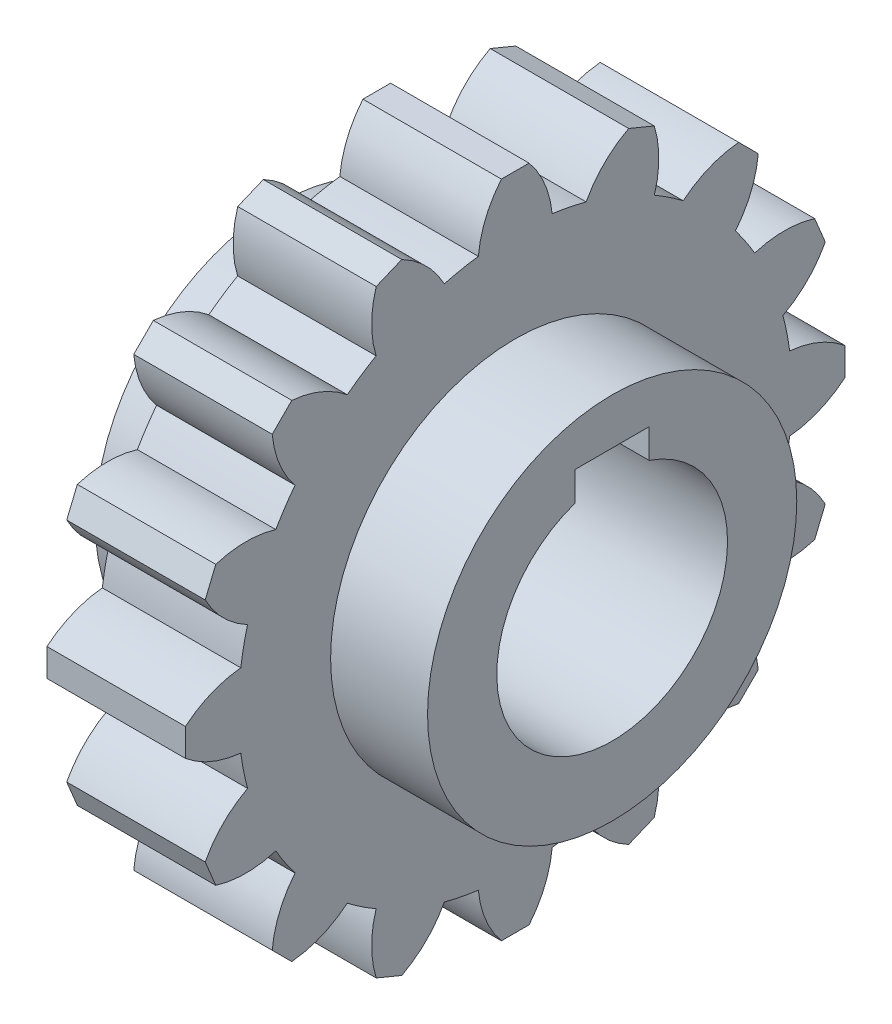
SolidWorks part; units mm, degrees
ref_plane "Ebene vorne" through (0, 0, 0) normal (0, 0, 1) x (1, 0, 0)
ref_plane "Ebene oben" through (0, 0, 0) normal (0, 1, 0) x (1, 0, 0)
ref_plane "Ebene rechts" through (0, 0, 0) normal (1, 0, 0) x (0, 0, -1)
sketch "Sketch1" plane through (0, 0, 0) normal (1, 0, 0) x (0, 0, -1)
  circle A0 centre (0, 0) radius 30
  dimension "D1" = 60
extrude "Boss-Extrude1" add sketch "Sketch1" along normal mid plane 15
sketch "Sketch2" plane through (7.5, 0, 0) normal (1, 0, 0) x (0, 0, -1)
  line L0 (0, 0) -> (0, 42.7215) construction
  line L1 (-1.5, 35.7321) -> (1.5, 35.7321)
  arc A0 (-4, 29.7321) -> (4, 29.7321) centre (0, 0) cw
  circle A1 centre (0, 0) radius 30
  circle A2 centre (0, 0) radius 30
  arc A3 (-4, 29.7321) -> (-1.5, 35.7321) centre (6.9505, 28.6902) cw
  arc A4 (4, 29.7321) -> (1.5, 35.7321) centre (-6.9505, 28.6902) ccw
  dimension "D6" = 11
  dimension "D2" = 4
  dimension "D3" = 1.5
  dimension "D4" = 1.5
  dimension "D5" = 6
  dimension "D1" = 0
extrude "Boss-Extrude2" add sketch "Sketch2" against normal up to surface (15 mm away) contours A4 L1 A3 A0 up to face at (-7.5, 0, -30)
pattern_circular "CirPattern1" count 16 over 360 about axis through (0, 0, 0) along (1, 0, 0) of "Boss-Extrude2"
sketch "Sketch3" plane through (0, 0, 0) normal (1, 0, 0) x (0, 0, -1)
  circle A0 centre (0, 0) radius 20
  dimension "D1" = 40
extrude "Boss-Extrude3" add sketch "Sketch3" along normal mid plane 36
sketch "Sketch4" plane through (-18, 0, 0) normal (-1, 0, 0) x (0, 0, 1)
  line L0 (0, 0) -> (0, 24.3564) construction
  line L1 (-4, 15) -> (4, 15)
  line L2 (4, 15) -> (4, 11.8427)
  line L3 (-4, 15) -> (-4, 11.8427)
  arc A0 (-4, 11.8427) -> (4, 11.8427) centre (0, 0) ccw
  dimension "D1" = 25
  dimension "D2" = 8
  dimension "D3" = 15
extrude "Cut-Extrude1" cut sketch "Sketch4" against normal through all both and the other way through all
